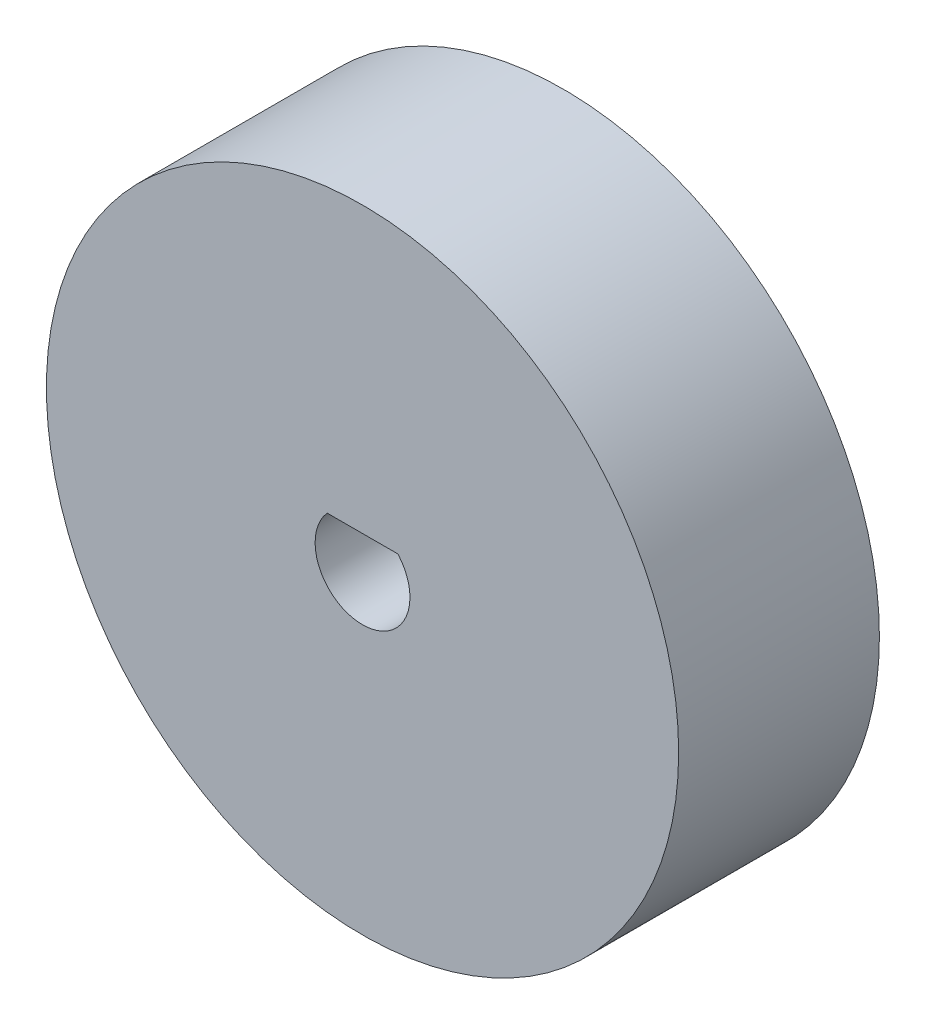
SolidWorks part; units mm, degrees
ref_plane "Front Plane" through (0, 0, 0) normal (0, 0, 1) x (1, 0, 0)
ref_plane "Top Plane" through (0, 0, 0) normal (0, 1, 0) x (1, 0, 0)
ref_plane "Right Plane" through (0, 0, 0) normal (1, 0, 0) x (0, 0, -1)
sketch "Sketch1" plane through (0, 0, 0) normal (0, 0, 1) x (1, 0, 0)
  circle A0 centre (0, 0) radius 10
  dimension "D1" = 20
extrude "Boss-Extrude1" add sketch "Sketch1" along normal blind 6.35
sketch "Sketch2" plane through (0, 0, 6.35) normal (0, 0, 1) x (1, 0, 0)
  line L0 (-1.118, 1) -> (1.118, 1)
  arc A0 (-1.118, 1) -> (1.118, 1) centre (0, 0) ccw
  dimension "D1" = 3
  dimension "D2" = 1
extrude "Cut-Extrude1" cut sketch "Sketch2" against normal through all both and the other way through all
equation "\"Wheel Thickness\"= 1in"
equation "\"Wheel Diameter\"= 3in"
equation "\"Motor Rear Diameter\" = 36.2mm"
equation "\"Motor Front Diameter\" = 12mm"
equation "\"Material Thickness\" = .25in"
equation "\"Wheel Cutout Diameter\"= 2cm"
equation "\"Motor Mount Tab Thickness\" = 100mm"
equation "\"Motor Mount Tab Height\" = 40mm"
equation "\"D1@Sketch1\"=\"Wheel Cutout Diameter\""
equation "\"D1@Boss-Extrude1\"=\"Shaft Attachment Thickness\""
equation "\"Motor Shaft Diameter\" = 3mm"
equation "\"D1@Sketch2\"=\"Motor Shaft Diameter\""
equation "\"D2@Sketch2\"=(\"Motor Shaft Diameter\"/2)-.5mm"
equation "\"Base Diameter\" = 10in"
equation "\"Distance Between Mounts\"= 1in"
equation "\"Shaft Attachment Thickness\"= .25in"
